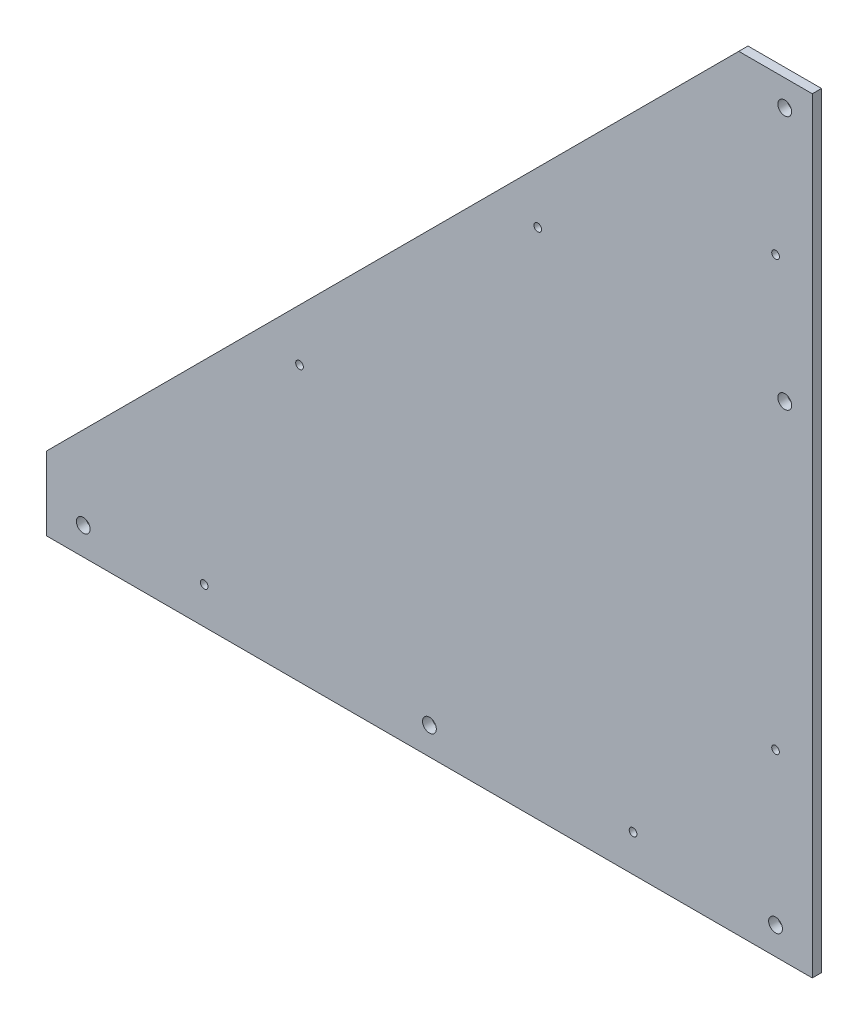
SolidWorks part; units mm, degrees
ref_plane "Plan de face" through (0, 0, 0) normal (0, 0, 1) x (1, 0, 0)
ref_plane "Plan de dessus" through (0, 0, 0) normal (0, 1, 0) x (1, 0, 0)
ref_plane "Plan de droite" through (0, 0, 0) normal (1, 0, 0) x (0, 0, -1)
sketch "Esquisse1" plane through (0, 0, 0) normal (0, 0, 1) x (1, 0, 0)
  line L0 (0, 0) -> (0, 48)
  line L1 (0, 48) -> (452, 500)
  line L4 (452, 500) -> (500, 500)
  line L5 (500, 500) -> (500, 0)
  line L6 (500, 0) -> (0, 0)
  dimension "D1" = 500
  dimension "D2" = 48
  dimension "D3" = 48
  dimension "D4" = 45
extrude "Boss.-Extru.1" add sketch "Esquisse1" along normal blind 6
sketch "Esquisse2" plane through (0, 0, 6) normal (0, 0, 1) x (1, 0, 0)
  line L0 (0, 48) -> (0, 0) construction
  line L1 (500, 0) -> (500, 500) construction
  line L2 (0, 0) -> (500, 0) construction
  circle A0 centre (24, 18) radius 4.5
  circle A1 centre (250, 18) radius 4.5
  circle A2 centre (476, 18) radius 4.5
  circle A5 centre (482, 483) radius 4.5
  circle A6 centre (482, 317) radius 4.5
  dimension "D5" = 9
  dimension "D1" = 24
  dimension "D2" = 24
  dimension "D3" = 250
  dimension "D4" = 18
  dimension "D6" = 166
  dimension "D7" = 317
  dimension "D8" = 18
extrude "Enlèv. mat.-Extru.1" cut sketch "Esquisse2" against normal through all
sketch "Esquisse4" [suppressed] plane through (0, 0, 6) normal (0, 0, 1) x (1, 0, 0)
  line L0 (222.5, 277.5) -> (500, 0) construction
  line L1 (445, 500) -> (0, 55) construction
  line L2 (384.3921, 398.4506) -> (101.5494, 115.6079) construction
  circle A0 centre (384.3921, 398.4506) radius 4.5
  circle A1 centre (101.5494, 115.6079) radius 4.5
  point P7 (242.9707, 257.0293)
  dimension "D1" = 9
  dimension "D2" = 400
  dimension "D3" = 28.95
extrude "Enlèv. mat.-Extru.2" [suppressed] cut sketch "Esquisse4" against normal through all
sketch "Esquisse5" plane through (0, 0, 6) normal (0, 0, 1) x (1, 0, 0)
  line L0 (9.9411, 24) -> (476, 490.0589) construction
  line L1 (476, 490.0589) -> (476, 24) construction
  line L2 (476, 24) -> (9.9411, 24) construction
  line L3 (452, 500) -> (0, 48) construction
  line L4 (500, 0) -> (500, 500) construction
  line L5 (0, 0) -> (500, 0) construction
  line L6 (242.9706, 257.0294) -> (476, 24) construction
  line L7 (242.9706, 257.0294) -> (242.9706, 24) construction
  line L8 (242.9706, 257.0294) -> (476, 257.0294) construction
  circle A0 centre (165.1888, 179.2477) radius 2.5
  circle A1 centre (320.7523, 334.8112) radius 2.5
  circle A2 centre (102.9706, 24) radius 2.5
  circle A3 centre (382.9706, 24) radius 2.5
  circle A4 centre (476, 397.0294) radius 2.5
  circle A5 centre (476, 117.0294) radius 2.5
  dimension "D4" = 5
  dimension "D1" = 24
  dimension "D2" = 24
  dimension "D3" = 24
  dimension "D5" = 220
  dimension "D6" = 280
  dimension "D7" = 280
extrude "Enlèv. mat.-Extru.3" cut sketch "Esquisse5" against normal through all
chamfer "Chanfrein1" [suppressed] distance 2 angle 45
chamfer "Chanfrein2" distance 2 angle 45 6 edges at (478.5, 117.0294, 0) (385.4706, 24, 0) (105.4706, 24, 0) (167.6888, 179.2477, 0) (323.2523, 334.8112, 0) (478.5, 397.0294, 0)
